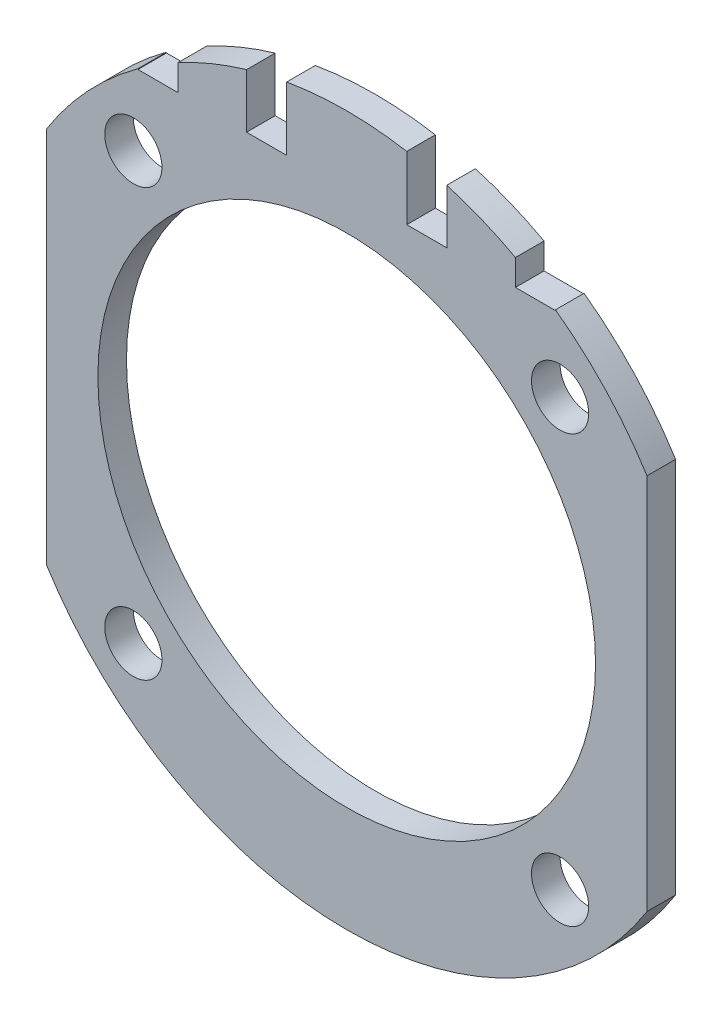
SolidWorks part; units mm, degrees
material "AISI 304"
ref_plane "Спереди" through (0, 0, 0) normal (0, 0, 1) x (1, 0, 0)
ref_plane "Сверху" through (0, 0, 0) normal (0, 1, 0) x (1, 0, 0)
ref_plane "Справа" through (0, 0, 0) normal (1, 0, 0) x (0, 0, -1)
sketch "Эскиз1" plane through (0, 0, 0) normal (0, 0, 1) x (1, 0, 0)
  line L0 (74.5998, 74.5998) -> (0, 0) construction
  line L1 (0, 0) -> (0, 105.5) construction
  circle A0 centre (0, 0) radius 124
  circle A1 centre (0, 0) radius 87
  circle A2 centre (0, 0) radius 105.5 construction
  circle A3 centre (74.5998, 74.5998) radius 10
  circle A4 centre (74.5998, -74.5998) radius 10
  circle A5 centre (-74.5998, -74.5998) radius 10
  circle A6 centre (-74.5998, 74.5998) radius 10
  point P17 (0, 0)
  dimension "D1" = 248
  dimension "D2" = 211
  dimension "D3" = 174
  dimension "D5" = 20
  dimension "D4" = 45
  dimension "D6" = 4
extrude "Бобышка-Вытянуть1" add sketch "Эскиз1" along normal mid plane 10
sketch "Эскиз2" plane through (0, 0, 5) normal (0, 0, 1) x (1, 0, 0)
  line L1 (-105, -140) -> (105, -140)
  line L2 (-105, -140) -> (-105, 140)
  line L3 (-105, 140) -> (105, 140)
  line L4 (105, -140) -> (105, 140)
  line L5 (-105, -140) -> (105, 140) construction
  line L6 (-105, 140) -> (105, -140) construction
  point P0 (0, 0)
  dimension "D1" = 210
  dimension "D2" = 280
extrude "Вырез-Вытянуть1" cut sketch "Эскиз2" against normal through all both and the other way through all flip side to cut
sketch "Эскиз3" plane through (0, 0, 5) normal (0, 0, 1) x (1, 0, 0)
  line L13 (-62, 145) -> (-70, 145) construction
  line L16 (70, 103) -> (70, 145) construction
  line L17 (70, 145) -> (62, 145) construction
  line L18 (62, 145) -> (62, 103) construction
  line L19 (62, 103) -> (70, 103) construction
  line L28 (-62, 103) -> (-62, 145) construction
  line L29 (-62, 145) -> (-70, 145) construction
  line L30 (-70, 145) -> (-70, 103) construction
  line L31 (-70, 103) -> (-62, 103) construction
  line L32 (-59, 148) -> (-73, 148)
  line L33 (-73, 148) -> (-73, 100)
  line L34 (-73, 100) -> (-59, 100)
  line L35 (-59, 100) -> (-59, 148)
  line L44 (59, 148) -> (59, 100)
  line L45 (59, 100) -> (73, 100)
  line L46 (73, 100) -> (73, 148)
  line L47 (73, 148) -> (59, 148)
  line L48 (35, 148) -> (21, 148)
  line L53 (32, 145) -> (24, 145) construction
  line L54 (32, 145) -> (32, 103) construction
  line L55 (32, 103) -> (24, 103) construction
  line L56 (24, 145) -> (24, 103) construction
  line L57 (-24, 103) -> (-32, 103) construction
  line L58 (-24, 103) -> (-24, 145) construction
  line L59 (-24, 145) -> (-32, 145) construction
  line L60 (-32, 103) -> (-32, 145) construction
  line L61 (21, 148) -> (21, 100)
  line L62 (35, 100) -> (21, 100)
  line L63 (35, 148) -> (35, 100)
  line L64 (-21, 148) -> (-35, 148)
  line L65 (-35, 100) -> (-35, 148)
  line L66 (-21, 100) -> (-35, 100)
  line L67 (-21, 100) -> (-21, 148)
  dimension "D1" = 3
  dimension "D2" = 3
extrude "Вырез-Вытянуть2" cut sketch "Эскиз3" against normal through all both and the other way through all
